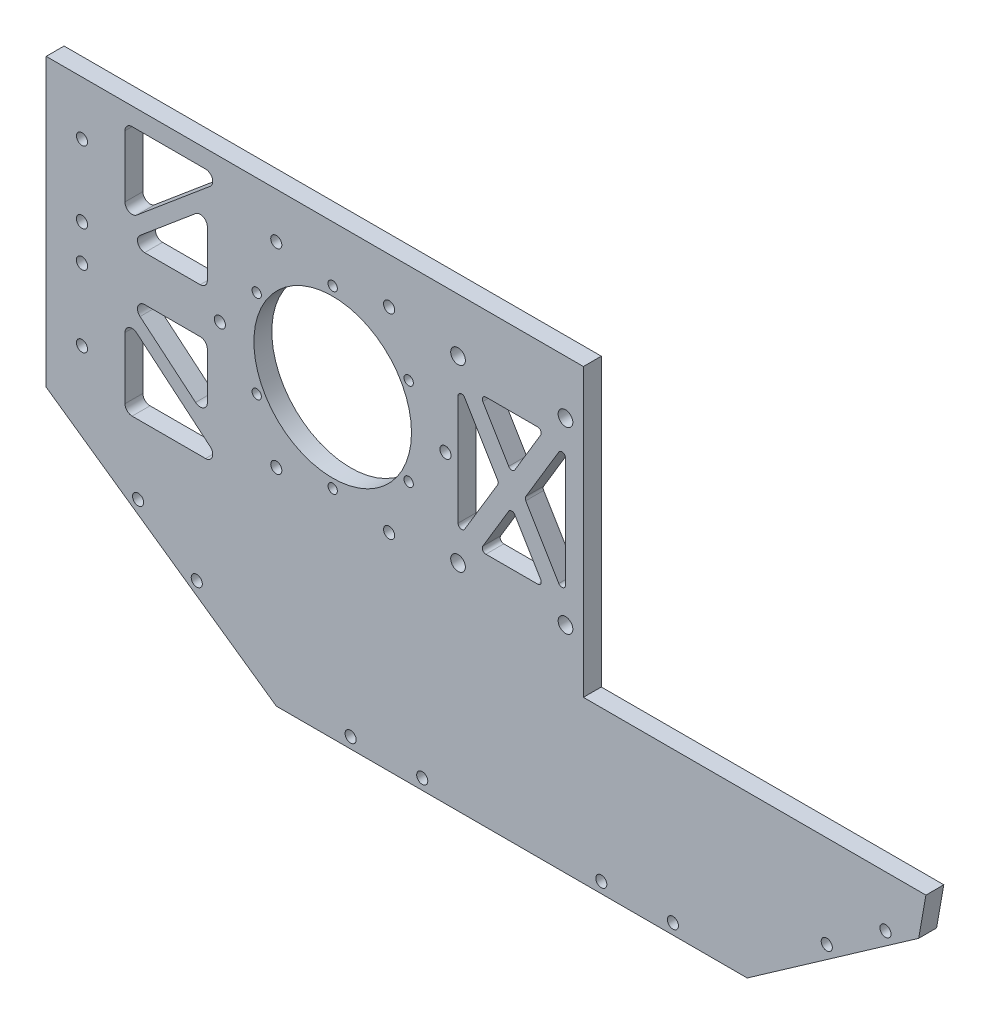
SolidWorks part; units mm, degrees
ref_plane "前视基准面" through (0, 0, 0) normal (0, 0, 1) x (1, 0, 0)
ref_plane "上视基准面" through (0, 0, 0) normal (0, 1, 0) x (1, 0, 0)
ref_plane "右视基准面" through (0, 0, 0) normal (1, 0, 0) x (0, 0, -1)
sketch "草图1" plane through (0, 0, 0) normal (0, 0, 1) x (1, 0, 0)
  line L1 (-80, 40) -> (70, 40)
  line L2 (-80, 40) -> (-80, -40)
  line L3 (-80, -40) -> (70, -40)
  line L4 (70, 40) -> (70, -40)
  circle A0 centre (0, 0) radius 24.5 construction
  circle A1 centre (0, -24.5) radius 1.3
  circle A2 centre (-21.2176, -12.25) radius 1.3
  circle A3 centre (-21.2176, 12.25) radius 1.3
  circle A4 centre (0, 0) radius 22
  circle A5 centre (0, 24.5) radius 1.3
  circle A6 centre (21.2176, 12.25) radius 1.3
  circle A7 centre (21.2176, -12.25) radius 1.3
  point P11 (0, 0)
  point P15 (70, 0)
  dimension "D1" = 49
  dimension "D2" = 2.6
  dimension "D4" = 44
  dimension "D5" = 80
  dimension "D6" = 70
  dimension "D7" = 80
  dimension "D3" = 6
extrude "凸台-拉伸1" add sketch "草图1" along normal blind 5
sketch "草图3" plane through (0, 0, 5) normal (0, 0, 1) x (1, 0, 0)
  line L0 (0, 0) -> (-70, 0) construction
  line L1 (-70, 0) -> (-70, -25) construction
  line L3 (-70, 0) -> (-70, 24.3133)
  circle A4 centre (-70, -25) radius 1.55
  circle A5 centre (-70, -5) radius 1.5828
  circle A6 centre (-70, 25) radius 1.55
  circle A7 centre (-70, 5) radius 1.5828
  point P6 (-70, 0)
  dimension "D3" = 3.1
  dimension "D4" = 20
  dimension "D1" = 70
  dimension "D2" = 25
extrude "切除-拉伸3" cut sketch "草图3" against normal blind 12.5
sketch "草图4" plane through (0, 0, 5) normal (0, 0, 1) x (1, 0, 0)
  line L0 (-58, 35) -> (-30, 35)
  line L1 (-30, 35) -> (-58, 11.5052)
  line L2 (-58, 11.5052) -> (-58, 35)
  line L3 (-35, 25.5829) -> (-58, 6.2836)
  line L4 (-58, 6.2836) -> (-35, 6.2836)
  line L5 (-35, 6.2836) -> (-35, 25.5829)
  line L8 (70, 40) -> (-80, 40) construction
  line L9 (-80, 40) -> (-80, -40) construction
  dimension "D1" = 5
  dimension "D2" = 22
  dimension "D3" = 140
  dimension "D4" = 45
  dimension "D6" = 4
extrude "切除-拉伸5" cut sketch "草图4" against normal blind 8 contours L2 L0 L1 | L5 L3 L4
fillet "圆角3" radius 2 6 edges at (-35, 6.2836, 2.5) (-58, 6.2836, 2.5) (-35, 25.5829, 2.5) (-30, 35, 2.5) (-58, 11.5052, 2.5) (-58, 35, 2.5)
mirror "镜向2" about plane through (0, 0, 0) normal (0, 1, 0) of "圆角3", "切除-拉伸5"
sketch "草图10" plane through (0, 0, 5) normal (0, 0, 1) x (1, 0, 0)
  line L0 (-80, -40) -> (-127.0531, -7.0531)
  line L1 (-127.0531, -7.0531) -> (-80, 40)
  line L2 (-80, -40) -> (70, -40) construction
  line L3 (-80, 40) -> (-80, -40) construction
  line L4 (-80, 40) -> (-80, -40)
  dimension "D1" = 145
  dimension "D2" = 45
extrude "凸台-拉伸4" add sketch "草图10" against normal up to surface (5 mm away) contours L4 L0 L1 up to face at (-49.3474, 27.3903, 0)
fillet "圆角5" radius 5 1 edges at (-127.0531, -7.0531, 2.5)
sketch "草图11" plane through (0, 0, 5) normal (0, 0, 1) x (1, 0, 0)
  line L0 (0, 0) -> (0, 34) construction
  line L1 (0, 0) -> (-15.75, 27.2798)
  circle A0 centre (0, 0) radius 29 construction
  circle A1 centre (0, 0) radius 34 construction
  circle A2 centre (0, 0) radius 31.5 construction
  circle A3 centre (-15.75, 27.2798) radius 1.55
  circle A4 centre (15.75, 27.2798) radius 1.55
  circle A5 centre (31.5, 0) radius 1.55
  circle A6 centre (15.75, -27.2798) radius 1.55
  circle A7 centre (-15.75, -27.2798) radius 1.55
  circle A8 centre (-31.5, 0) radius 1.55
  point P20 (0, 0)
  dimension "D1" = 58
  dimension "D2" = 68
  dimension "D3" = 63
  dimension "D5" = 3.1
  dimension "D4" = 30
  dimension "D6" = 6
extrude "切除-拉伸7" cut sketch "草图11" against normal blind 25 contours A3 | A4 | A5 | A6 | A7 | A8
sketch "草图12" plane through (0, 0, 5) normal (0, 0, 1) x (1, 0, 0)
  line L0 (0, 0) -> (50, 0) construction
  line L6 (35, -25) -> (65, -25) construction
  line L7 (35, -25) -> (35, 25) construction
  line L8 (35, 25) -> (65, 25) construction
  line L9 (65, -25) -> (65, 25) construction
  line L10 (35, -25) -> (65, 25) construction
  line L11 (35, 25) -> (65, -25) construction
  circle A0 centre (0, 0) radius 28 construction
  circle A1 centre (35, 25) radius 2.05
  circle A2 centre (65, 25) radius 2.05
  circle A3 centre (65, -25) radius 2.05
  circle A4 centre (35, -25) radius 2.05
  dimension "D3" = 56
  dimension "D5" = 4.1
  dimension "D6" = 4.1
  dimension "D1" = 30
  dimension "D2" = 50
  dimension "D4" = 50
extrude "切除-拉伸8" cut sketch "草图12" against normal blind 10
sketch "草图13" plane through (0, 0, 5) normal (0, 0, 1) x (1, 0, 0)
  line L0 (35, 25) -> (65, -25) construction
  line L6 (35, 25) -> (65, -25) construction
  line L10 (35, 19) -> (35, -19)
  line L11 (35, -19) -> (46.4, 0)
  line L12 (46.4, 0) -> (35, 19)
  line L13 (35, -25) -> (65, 25) construction
  line L14 (50, 0) -> (50, -49.4768) construction
  line L15 (65, -19) -> (53.6, 0)
  line L16 (65, 19) -> (65, -19)
  line L17 (53.6, 0) -> (65, 19)
  line L18 (41, 19) -> (50, 4)
  line L19 (50, 4) -> (59, 19)
  line L20 (59, 19) -> (41, 19)
  line L21 (35, 19) -> (65, 19) construction
  line L22 (50, 0) -> (90.4004, 0) construction
  line L23 (50, -4) -> (59, -19)
  line L24 (41, -19) -> (50, -4)
  line L25 (59, -19) -> (41, -19)
  circle A0 centre (35, -25) radius 2.05 construction
  circle A1 centre (65, 25) radius 2.05 construction
  point P4 (50, 0)
  dimension "D1" = 6
  dimension "D2" = 6
  dimension "D3" = 6
  dimension "D4" = 6
  dimension "D5" = 0
extrude "切除-拉伸9" cut sketch "草图13" against normal blind 10
fillet "圆角6" radius 1 12 edges at (35, -19, 2.5) (46.4, 0, 2.5) (35, 19, 2.5) (41, -19, 2.5) (50, -4, 2.5) (59, -19, 2.5) (65, -19, 2.5) (65, 19, 2.5) (53.6, 0, 2.5) (50, 4, 2.5) (59, 19, 2.5) (41, 19, 2.5)
sketch "草图14" plane through (0, 0, 0) normal (0, 0, -1) x (-1, 0, 0)
  circle A0 centre (0, 24.5) radius 2.25
  circle A1 centre (21.2176, 12.25) radius 2.25
  circle A2 centre (21.2176, -12.25) radius 2.25
  circle A3 centre (0, -24.5) radius 2.25
  circle A4 centre (-21.2176, -12.25) radius 2.25
  circle A5 centre (-21.2176, 12.25) radius 2.25
  point P15 (0, 0)
  dimension "D1" = 4.5
  dimension "D2" = 6
extrude "切除-拉伸10" cut sketch "草图14" against normal blind 2.5
sketch "草图15" plane through (0, 0, 0) normal (0, 0, -1) x (-1, 0, 0)
  line L0 (-50, 19) -> (-50, -132.8609) construction
  line L2 (-57.2338, 19) -> (-42.7662, 19) construction
  line L3 (80, -40) -> (15.7333, -85)
  line L4 (15.7333, -85) -> (-115.7333, -85)
  line L5 (80, -40) -> (-70, -40) construction
  line L6 (122.1719, -10.4709) -> (80, -40) construction
  line L7 (80, -40) -> (-180, -40)
  line L8 (-50, -85) -> (-50, -40)
  line L9 (-180, -40) -> (-115.7333, -85)
  dimension "D1" = 180
  dimension "D2" = 45
extrude "凸台-拉伸5" add sketch "草图15" against normal up to surface (5 mm away) contours L8 L4 L3 L7 | L7 L9 L4 L8 up to face at (50, 13.974, 5)
chamfer "倒角1" distance 20 angle 45 1 edges at (180, -40, 2.5)
sketch "草图16" plane through (0, 0, 0) normal (0, 0, -1) x (-1, 0, 0)
  line L0 (-50, -85) -> (-50, -82)
  line L1 (15.7333, -85) -> (-115.7333, -85) construction
  line L2 (-50, -82) -> (-75, -82) construction
  line L3 (-50, -82) -> (-50, -114.8278) construction
  circle A0 centre (-75, -82) radius 1.55
  circle A1 centre (-95, -82) radius 1.55
  circle A2 centre (-25, -82) radius 1.55
  circle A3 centre (-5, -82) radius 1.55
  dimension "D3" = 3.1
  dimension "D1" = 3
  dimension "D2" = 25
  dimension "D4" = 2
extrude "切除-拉伸11" cut sketch "草图16" against normal blind 10.5 contours A1 | A0 | A2 | A3
sketch "草图17" plane through (0, 0, 5) normal (0, 0, 1) x (1, 0, 0)
  line L0 (50, 19) -> (50, -19)
  line L1 (57.2338, 19) -> (42.7662, 19) construction
  line L2 (42.7662, -19) -> (57.2338, -19) construction
  line L3 (50, 0) -> (-80, 0)
  line L4 (-80, 0) -> (-80, 40)
  line L5 (-122.8396, -2.8396) -> (-80, 40) construction
  line L6 (-80, 40) -> (-122.8396, -2.8396)
  line L7 (-80, 0) -> (-80, -40)
  line L8 (-15.7333, -85) -> (-122.1719, -10.4709) construction
  line L9 (-80, -40) -> (-122.1719, -10.4709)
  arc A0 (-122.8396, -2.8396) -> (-122.1719, -10.4709) centre (-119.3041, -6.3751) ccw construction
  arc A1 (-122.8396, -2.8396) -> (-122.1719, -10.4709) centre (-119.3041, -6.3751) ccw
  dimension "D1" = 130
extrude "切除-拉伸12" cut sketch "草图17" against normal blind 10 contours L6 A1 L9 L7 L4
sketch "草图18" plane through (0, 0, 5) normal (0, 0, 1) x (1, 0, 0)
  line L0 (-47.8667, -62.5) -> (-46.1459, -60.0425) construction
  line L1 (-15.7333, -85) -> (-80, -40) construction
  line L2 (-54.3375, -54.3068) -> (-37.9544, -65.7783) construction
  line L3 (50, 19) -> (50, -118.2757) construction
  line L4 (57.2338, 19) -> (42.7662, 19) construction
  circle A0 centre (-54.3375, -54.3068) radius 1.55
  circle A1 centre (-37.9544, -65.7783) radius 1.55
  circle A4 centre (137.9544, -65.7783) radius 1.55
  circle A5 centre (154.3375, -54.3068) radius 1.55
  point P7 (-46.1459, -60.0425)
  dimension "D3" = 3.1
  dimension "D4" = 3.1
  dimension "D1" = 3
  dimension "D2" = 20
extrude "切除-拉伸13" cut sketch "草图18" against normal blind 13
